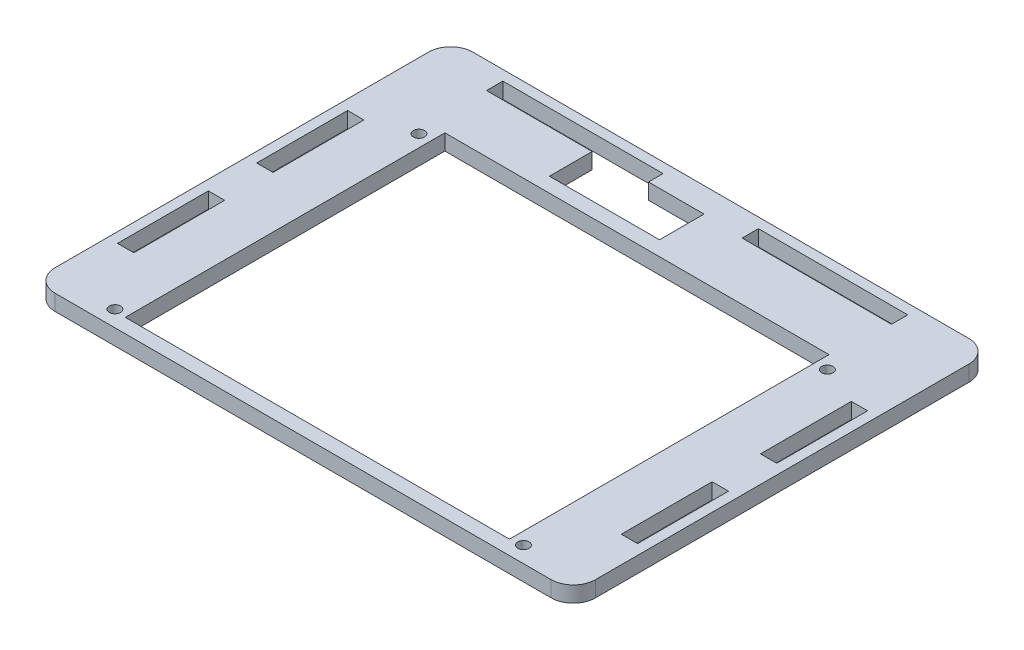
SolidWorks part; units mm, degrees
ref_plane "Front Plane" through (0, 0, 0) normal (0, 0, 1) x (1, 0, 0)
ref_plane "Top Plane" through (0, 0, 0) normal (0, 1, 0) x (1, 0, 0)
ref_plane "Right Plane" through (0, 0, 0) normal (1, 0, 0) x (0, 0, -1)
sketch "Sketch1" plane through (0, 0, 0) normal (0, 1, 0) x (1, 0, 0)
  line L0 (-38.5572, -41.9227) -> (-38.5572, 25.0825)
  line L1 (-54.229, 41.9227) -> (54.229, 41.9227)
  line L2 (-54.229, 41.9227) -> (-54.229, -41.9227)
  line L3 (-54.229, -41.9227) -> (-38.5572, -41.9227)
  line L4 (54.229, 41.9227) -> (54.229, -41.9227)
  line L5 (-38.5572, 25.0825) -> (38.5572, 25.0825)
  line L6 (38.5572, 25.0825) -> (38.5572, -41.9227)
  line L7 (38.5572, -41.9227) -> (54.229, -41.9227)
  line L8 (-51.943, 18.9357) -> (-51.943, 1.2065) construction
  line L9 (-51.943, -9.0043) -> (-49.1744, -9.0043) construction
  line L10 (-51.943, -9.0043) -> (-51.943, -26.7335) construction
  line L11 (-51.943, -26.7335) -> (-49.1744, -26.7335) construction
  line L12 (-49.1744, -9.0043) -> (-49.1744, -26.7335) construction
  line L13 (-49.1744, 18.9357) -> (-49.1744, 1.2065) construction
  line L14 (-51.943, 18.9357) -> (-49.1744, 18.9357) construction
  line L15 (-51.943, 1.2065) -> (-49.1744, 1.2065) construction
  line L16 (0, -1000) -> (0, 49000) construction
  line L17 (51.943, -26.7335) -> (49.1744, -26.7335) construction
  line L18 (49.1744, -9.0043) -> (49.1744, -26.7335) construction
  line L19 (51.943, -9.0043) -> (51.943, -26.7335) construction
  line L20 (51.943, -9.0043) -> (49.1744, -9.0043) construction
  line L21 (51.943, 1.2065) -> (49.1744, 1.2065) construction
  line L22 (51.943, 18.9357) -> (51.943, 1.2065) construction
  line L23 (51.943, 18.9357) -> (49.1744, 18.9357) construction
  line L24 (49.1744, 18.9357) -> (49.1744, 1.2065) construction
  line L25 (-20.2692, 36.8681) -> (-41.4782, 36.8681) construction
  line L26 (-41.4782, 36.8681) -> (-41.4782, 39.6367) construction
  line L27 (-9.8298, 39.6367) -> (-9.8298, 36.9697) construction
  line L28 (-9.8298, 36.9697) -> (1.3208, 36.9697) construction
  line L29 (1.3208, 36.9697) -> (1.3208, 28.2829) construction
  line L30 (1.3208, 28.2829) -> (-20.2692, 28.2829) construction
  line L31 (-20.2692, 28.2829) -> (-20.2692, 36.8681) construction
  line L32 (-41.4782, 39.6367) -> (-9.8298, 39.6367) construction
  line L33 (9.8298, 38.591) -> (9.8298, 39.6367) construction
  line L34 (9.8298, 39.6367) -> (39.2938, 39.6367) construction
  line L35 (39.2938, 39.6367) -> (39.2938, 36.8681) construction
  line L36 (39.2938, 36.8681) -> (44.2722, 36.8681) construction
  line L37 (44.2722, 36.8681) -> (44.2722, 31.0261) construction
  line L38 (44.2722, 31.0261) -> (36.0172, 31.0261) construction
  line L39 (36.0172, 31.0261) -> (36.0172, 36.8681) construction
  line L40 (36.0172, 36.8681) -> (9.8298, 36.8681) construction
  line L41 (9.8298, 36.8681) -> (9.8298, 38.591) construction
  line L42 (-52.197, 19.1897) -> (-52.197, 0.9525)
  line L43 (-52.197, 0.9525) -> (-48.9204, 0.9525)
  line L44 (-48.9204, 19.1897) -> (-48.9204, 0.9525)
  line L45 (-52.197, 19.1897) -> (-48.9204, 19.1897)
  line L46 (-52.197, -8.7503) -> (-48.9204, -8.7503)
  line L47 (-48.9204, -8.7503) -> (-48.9204, -26.9875)
  line L48 (-52.197, -26.9875) -> (-48.9204, -26.9875)
  line L49 (-52.197, -8.7503) -> (-52.197, -26.9875)
  line L50 (52.197, -26.9875) -> (48.9204, -26.9875)
  line L51 (48.9204, -8.7503) -> (48.9204, -26.9875)
  line L52 (52.197, -8.7503) -> (48.9204, -8.7503)
  line L53 (52.197, -8.7503) -> (52.197, -26.9875)
  line L54 (52.197, 0.9525) -> (48.9204, 0.9525)
  line L55 (48.9204, 19.1897) -> (48.9204, 0.9525)
  line L56 (52.197, 19.1897) -> (48.9204, 19.1897)
  line L57 (52.197, 19.1897) -> (52.197, 0.9525)
  line L58 (-20.5232, 36.6141) -> (-41.7322, 36.6141)
  line L59 (-41.7322, 36.6141) -> (-41.7322, 39.8907)
  line L60 (-41.7322, 39.8907) -> (-9.5758, 39.8907)
  line L61 (-9.5758, 39.8907) -> (-9.5758, 37.2237)
  line L62 (1.5748, 37.2237) -> (1.5748, 28.0289) construction
  line L63 (1.5748, 36.9697) -> (1.5748, 28.0289)
  line L64 (1.5748, 28.0289) -> (-20.5232, 28.0289)
  line L65 (-20.5232, 28.0289) -> (-20.5232, 36.6141)
  line L66 (9.5758, 38.591) -> (9.5758, 39.8907)
  line L67 (9.5758, 39.8907) -> (39.5478, 39.8907)
  line L68 (39.5478, 39.8907) -> (39.5478, 37.1221)
  line L69 (39.5478, 37.1221) -> (44.5262, 37.1221)
  line L70 (44.5262, 37.1221) -> (44.5262, 30.7721)
  line L71 (44.5262, 30.7721) -> (35.7632, 30.7721)
  line L72 (35.7632, 30.7721) -> (35.7632, 36.6141)
  line L73 (35.7632, 36.6141) -> (9.5758, 36.6141)
  line L74 (9.5758, 36.6141) -> (9.5758, 38.591)
  line L75 (-9.5758, 37.2237) -> (-9.5758, 36.9697)
  line L76 (-9.5758, 36.9697) -> (1.5748, 36.9697)
  line L77 (-9.5758, 37.2237) -> (1.5748, 37.2237) construction
  circle A0 centre (-40.9956, -38.6969) radius 1.1303
  circle A1 centre (-40.9956, 22.3139) radius 1.1303
  circle A2 centre (40.9956, 22.3139) radius 1.1303
  circle A3 centre (40.9956, -38.6969) radius 1.1303
  dimension "D8" = 2.2606
  dimension "D9" = 2.2606
  dimension "D10" = 2.2606
  dimension "D11" = 2.2606
  dimension "D1" = 83.8454
  dimension "D2" = 108.458
  dimension "D3" = 54.229
  dimension "D4" = 41.9227
  dimension "D5" = 15.6718
  dimension "D6" = 15.6718
  dimension "D7" = 67.0052
  dimension "D12" = 2.4384
  dimension "D13" = 3.2258
  dimension "D14" = 2.4384
  dimension "D15" = 3.2258
  dimension "D16" = 19.6088
  dimension "D17" = 2.4384
  dimension "D18" = 19.6088
  dimension "D19" = 2.4384
  dimension "D20" = 17.7292
  dimension "D21" = 2.7686
  dimension "D22" = 15.1892
  dimension "D23" = 2.286
  dimension "D25" = 2.667
  dimension "D26" = 11.1506
  dimension "D27" = 8.6868
  dimension "D28" = 21.59
  dimension "D29" = 8.5852
  dimension "D30" = 21.209
  dimension "D31" = 33.9598
  dimension "D32" = 2.286
  dimension "D33" = 26.1874
  dimension "D34" = 2.7686
  dimension "D35" = 4.9784
  dimension "D36" = 5.842
  dimension "D37" = 8.255
  dimension "D38" = 5.842
  dimension "D39" = 9.9568
  dimension "D40" = 2.286
  dimension "D41" = 0.254
  dimension "D42" = 0.254
  dimension "D24" = 2
extrude "Boss-Extrude1" add sketch "Sketch1" along normal mid plane 3.175
fillet "Fillet1" radius 4.445 4 edges at (54.229, 0, 41.9227) (54.229, 0, -41.9227) (-54.229, 0, -41.9227) (-54.229, 0, 41.9227)
sketch "Sketch2" plane through (0, 1.5875, 0) normal (0, 1, 0) x (1, 0, 0)
  line L0 (-40.9956, -39.8272) -> (40.9956, -39.8272)
  line L1 (40.9956, -39.8272) -> (40.9956, -41.9227)
  line L2 (38.5572, -41.9227) -> (49.784, -41.9227) construction
  line L3 (40.9956, -41.9227) -> (-40.9956, -41.9227)
  line L4 (-49.784, -41.9227) -> (-38.5572, -41.9227) construction
  line L5 (-40.9956, -41.9227) -> (-40.9956, -39.8272)
  circle A0 centre (-40.9956, -38.6969) radius 1.1303 construction
  circle A1 centre (40.9956, -38.6969) radius 1.1303 construction
extrude "Boss-Extrude2" add sketch "Sketch2" against normal blind 3.175
sketch "Sketch4" plane through (0, 1.5875, 0) normal (0, 1, 0) x (1, 0, 0)
  line L0 (35.7632, 36.6141) -> (39.5478, 36.6141)
  line L1 (44.5262, 37.1221) -> (39.5478, 37.1221)
  line L2 (44.5262, 37.1221) -> (44.5262, 30.7721)
  line L3 (44.5262, 30.7721) -> (35.7632, 30.7721)
  line L4 (35.7632, 36.6141) -> (35.7632, 30.7721)
  line L5 (39.5478, 37.1221) -> (39.5478, 36.6141)
extrude "Boss-Extrude3" add sketch "Sketch4" against normal through all
sketch "Sketch5" plane through (0, 1.5875, 0) normal (0, 1, 0) x (1, 0, 0)
  line L0 (38.5572, 25.0825) -> (38.5572, -39.8272) construction
  line L1 (-38.5572, -39.8272) -> (38.5572, -39.8272)
  line L2 (-38.5572, -39.8272) -> (-38.5572, -39.0652)
  line L3 (-38.5572, -39.0652) -> (38.5572, -39.0652)
  line L4 (38.5572, -39.8272) -> (38.5572, -39.0652)
  dimension "D1" = 0.762
extrude "Boss-Extrude4" add sketch "Sketch5" against normal blind 3.175
equation "\"D3@Sketch1\"=.5*\"D2@Sketch1\""
equation "\"D4@Sketch1\"=.5*\"D1@Sketch1\""
